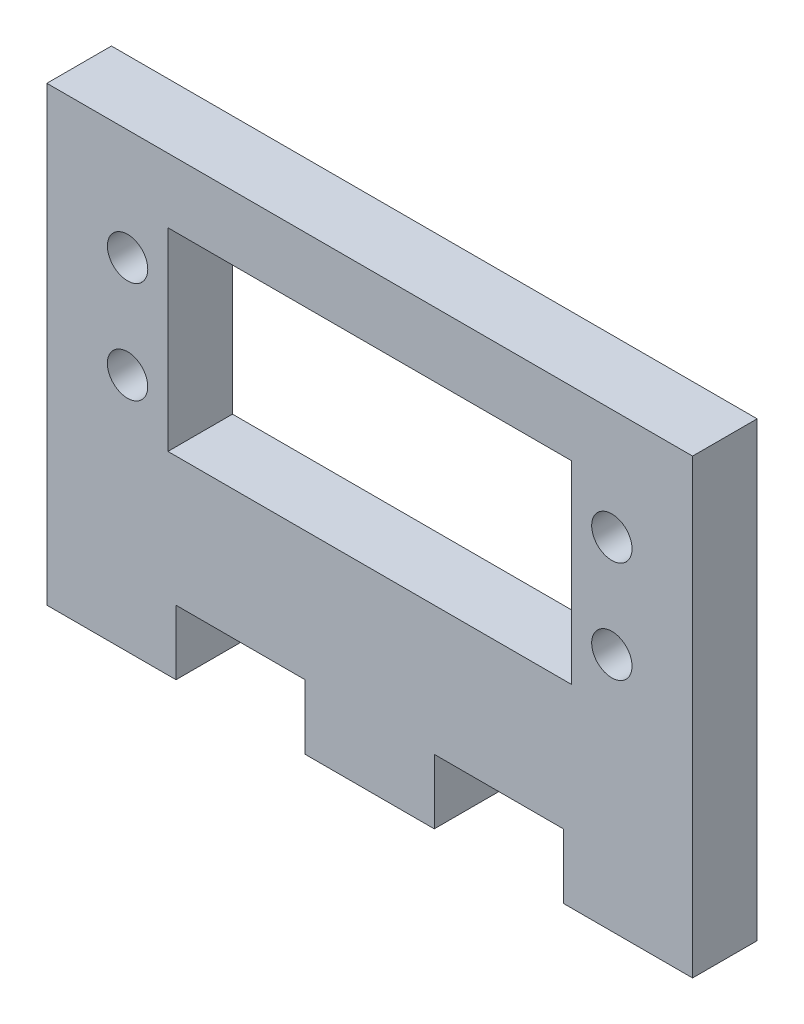
SolidWorks part; units mm, degrees
material "Mahogany"
ref_plane "Front" through (0, 0, 0) normal (0, 0, 1) x (1, 0, 0)
ref_plane "Top" through (0, 0, 0) normal (0, 1, 0) x (1, 0, 0)
ref_plane "Right" through (0, 0, 0) normal (1, 0, 0) x (0, 0, -1)
sketch "Sketch2" plane through (0, 0, 0) normal (0, 0, 1) x (1, 0, 0)
  line L0 (43.6562, 4.525) -> (43.6562, 14.525) construction
  line L1 (0, 0) -> (39.6875, 0)
  line L2 (0, 0) -> (0, 19.05)
  line L3 (0, 19.05) -> (39.6875, 19.05)
  line L4 (39.6875, 0) -> (39.6875, 19.05)
  line L5 (-11.9063, 25.4) -> (51.5938, 25.4)
  line L6 (-11.9063, 25.4) -> (-11.9063, -19.05)
  line L7 (-11.9063, -19.05) -> (51.5937, -19.05)
  line L8 (51.5938, 25.4) -> (51.5937, -19.05)
  line L9 (19.8437, 19.05) -> (19.8437, 0) construction
  line L10 (13.4937, -12.7) -> (0.7937, -12.7)
  line L11 (13.4937, -19.05) -> (26.1937, -19.05)
  line L12 (13.4937, -19.05) -> (13.4937, -12.7)
  line L13 (13.4937, -12.7) -> (26.1937, -12.7) construction
  line L14 (26.1937, -19.05) -> (26.1937, -12.7)
  line L15 (0.7937, -12.7) -> (0.7937, -19.05)
  line L16 (26.1937, -12.7) -> (38.8937, -12.7)
  line L17 (38.8937, -12.7) -> (38.8937, -19.05)
  circle A0 centre (43.6562, 14.525) radius 1.9844
  circle A1 centre (43.6562, 4.525) radius 1.9844
  circle A2 centre (-3.9688, 4.525) radius 1.9844
  circle A3 centre (-3.9688, 14.525) radius 1.9844
  point P9 (19.8438, 0)
  point P10 (19.8437, -19.05)
  point P15 (43.6562, 9.525)
  point P16 (39.6875, 9.525)
  point P27 (19.8437, -12.7)
  dimension "D6" = 10
  dimension "D7" = 3.9688
  dimension "D1" = 19.05
  dimension "D2" = 39.6875
  dimension "D3" = 44.45
  dimension "D4" = 19.05
  dimension "D5" = 63.5
  dimension "D8" = 3.9688
  dimension "D9" = 6.35
  dimension "D10" = 12.7
extrude "Boss-Extrude1" add sketch "Sketch2" along normal blind 6.35 contours L14 L7 L8 L5 L6 L12 L13 A2 A1 A0 L4 L1 L2 L3 A3
